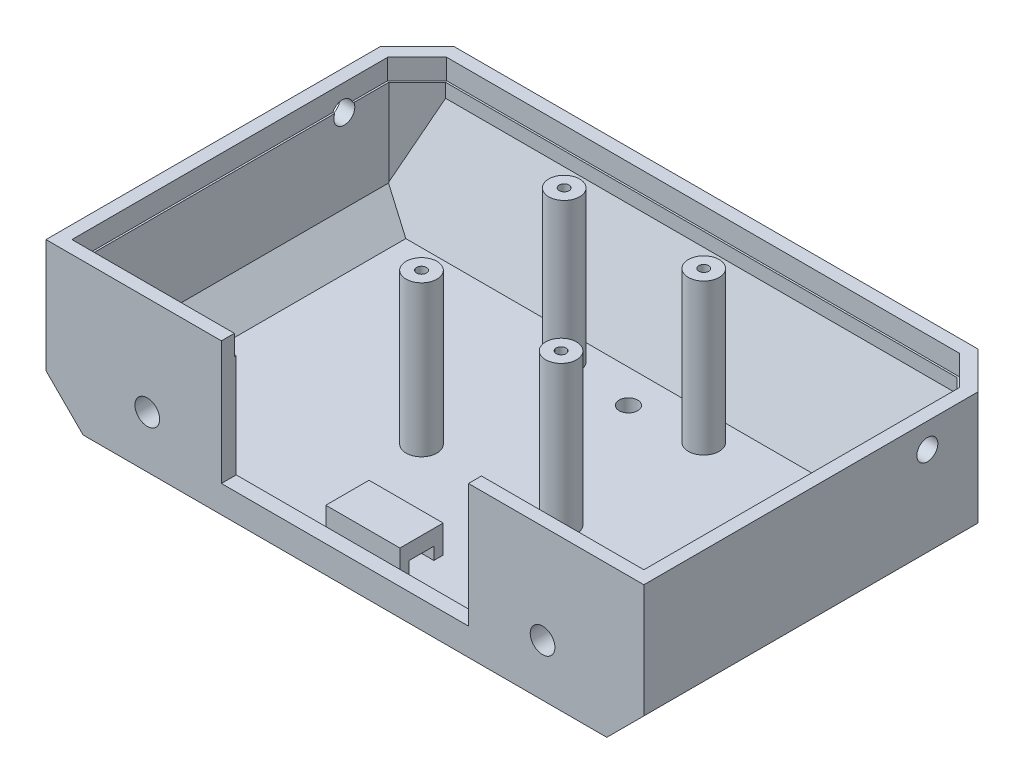
SolidWorks part; units mm, degrees
ref_plane "Front Plane" through (0, 0, 0) normal (0, 0, 1) x (1, 0, 0)
ref_plane "Top Plane" through (0, 0, 0) normal (0, 1, 0) x (1, 0, 0)
ref_plane "Right Plane" through (0, 0, 0) normal (1, 0, 0) x (0, 0, -1)
ref_plane "PZm28_4" through (0, -28.4, 0) normal (0, 1, 0) x (1, 0, 0)
sketch "Sketch1" plane through (0, -28.4, 0) normal (0, 1, 0) x (1, 0, 0)
  line L0 (-48.4, -11.9) -> (48.4, -11.9)
  line L1 (48.4, -11.9) -> (48.4, 42.2)
  line L2 (48.4, 42.2) -> (42.4, 48.2)
  line L3 (42.4, 48.2) -> (-42.4, 48.2)
  line L4 (-42.4, 48.2) -> (-48.4, 42.2)
  line L5 (-48.4, 42.2) -> (-48.4, -11.9)
extrude "Tray Block" add sketch "Sketch1" along normal blind 24.4
sketch "Sketch2" plane through (0, 0, 0) normal (1, 0, 0) x (0, 0, -1)
  line L0 (49.64, -6.32) -> (53.2, -6.32)
  line L1 (53.2, -6.32) -> (53.2, -32.08)
  line L2 (53.2, -32.08) -> (39.56, -32.08)
  line L3 (39.56, -32.08) -> (49.64, -6.32)
extrude "Lower Front Facet" cut sketch "Sketch2" against normal through all and the other way through all
sketch "Sketch3" plane through (0, 0, 0) normal (0, 0, 1) x (1, 0, 0)
  line L0 (-49.4, -21.4) -> (-49.4, -29.4)
  line L1 (-49.4, -29.4) -> (-41.4, -29.4)
  line L2 (-41.4, -29.4) -> (-49.4, -21.4)
extrude "Lower Side Facet L" cut sketch "Sketch3" against normal through all and the other way through all
sketch "Sketch4" plane through (0, 0, 0) normal (0, 0, 1) x (1, 0, 0)
  line L0 (49.4, -21.4) -> (49.4, -29.4)
  line L1 (49.4, -29.4) -> (41.4, -29.4)
  line L2 (41.4, -29.4) -> (49.4, -21.4)
extrude "Lower Side Facet R" cut sketch "Sketch4" against normal through all and the other way through all
shell "Shell" thickness 2.4
ref_plane "PZm7_3" through (0, -7.3, 0) normal (0, 1, 0) x (1, 0, 0)
sketch "Sketch5" plane through (0, -7.3, 0) normal (0, 1, 0) x (1, 0, 0)
  line L0 (-46.3, -9.8) -> (46.3, -9.8)
  line L1 (46.3, -9.8) -> (46.3, 41.3302)
  line L2 (46.3, 41.3302) -> (41.5302, 46.1)
  line L3 (41.5302, 46.1) -> (-41.5302, 46.1)
  line L4 (-41.5302, 46.1) -> (-46.3, 41.3302)
  line L5 (-46.3, 41.3302) -> (-46.3, -9.8)
extrude "Seam Rebate" cut sketch "Sketch5" along normal blind 4.3
ref_plane "PZm26_5" through (0, -26.5, 0) normal (0, 1, 0) x (1, 0, 0)
sketch "Sketch6" plane through (0, -26.5, 0) normal (0, 1, 0) x (1, 0, 0)
  circle A0 centre (-11.3, 11.8) radius 2.5
  circle A1 centre (-11.3, 34.9) radius 2.5
  circle A2 centre (11.3, 11.8) radius 2.5
  circle A3 centre (11.3, 34.9) radius 2.5
extrude "Board Pillars" add sketch "Sketch6" along normal blind 24.9
ref_plane "PZm9_6" through (0, -9.6, 0) normal (0, 1, 0) x (1, 0, 0)
sketch "Sketch7" plane through (0, -9.6, 0) normal (0, 1, 0) x (1, 0, 0)
  circle A0 centre (-11.3, 11.8) radius 0.8
  circle A1 centre (-11.3, 34.9) radius 0.8
  circle A2 centre (11.3, 11.8) radius 0.8
  circle A3 centre (11.3, 34.9) radius 0.8
extrude "Board Pilots" cut sketch "Sketch7" along normal blind 8.5
ref_plane "PY9" through (0, 0, 9) normal (0, 0, 1) x (1, 0, 0)
sketch "Sketch8" plane through (0, 0, 9) normal (0, 0, 1) x (1, 0, 0)
  line L0 (-20, -24) -> (20, -24)
  line L1 (20, -24) -> (20, -3)
  line L2 (20, -3) -> (-20, -3)
  line L3 (-20, -3) -> (-20, -24)
extrude "Cable Window" cut sketch "Sketch8" along normal blind 3.9
ref_plane "PY3_5" through (0, 0, 3.5) normal (0, 0, 1) x (1, 0, 0)
sketch "Sketch9" plane through (0, 0, 3.5) normal (0, 0, 1) x (1, 0, 0)
  circle A0 centre (-32, -20) radius 4
  circle A1 centre (32, -20) radius 4
extrude "Flange Bosses" add sketch "Sketch9" along normal blind 6.2
ref_plane "PY5_4" through (0, 0, 5.4) normal (0, 0, 1) x (1, 0, 0)
sketch "Sketch10" plane through (0, 0, 5.4) normal (0, 0, 1) x (1, 0, 0)
  circle A0 centre (-32, -20) radius 2
  circle A1 centre (32, -20) radius 2
extrude "Flange Insert Holes" cut sketch "Sketch10" along normal blind 7
ref_plane "PXm49_4" through (-49.4, 0, 0) normal (1, 0, 0) x (0, 0, -1)
sketch "Sketch11" plane through (-49.4, 0, 0) normal (1, 0, 0) x (0, 0, -1)
  circle A0 centre (34, -8) radius 1.7
extrude "Seam Screw Hole L" cut sketch "Sketch11" along normal blind 3.9
ref_plane "PX45_5" through (45.5, 0, 0) normal (1, 0, 0) x (0, 0, -1)
sketch "Sketch12" plane through (45.5, 0, 0) normal (1, 0, 0) x (0, 0, -1)
  circle A0 centre (34, -8) radius 1.7
extrude "Seam Screw Hole R" cut sketch "Sketch12" along normal blind 3.9
sketch "Sketch13" plane through (0, -26.5, 0) normal (0, 1, 0) x (1, 0, 0)
  line L0 (-6, -9) -> (6, -9)
  line L1 (6, -9) -> (6, -2)
  line L2 (6, -2) -> (-6, -2)
  line L3 (-6, -2) -> (-6, -9)
extrude "Bundle Tie Anchor" add sketch "Sketch13" along normal blind 5
ref_plane "PXm7" through (-7, 0, 0) normal (1, 0, 0) x (0, 0, -1)
sketch "Sketch14" plane through (-7, 0, 0) normal (1, 0, 0) x (0, 0, -1)
  line L0 (-7.5, -26) -> (-3.5, -26)
  line L1 (-3.5, -26) -> (-3.5, -24)
  line L2 (-3.5, -24) -> (-7.5, -24)
  line L3 (-7.5, -24) -> (-7.5, -26)
extrude "Bundle Tie Slot" cut sketch "Sketch14" along normal blind 14
ref_plane "PZm29_4" through (0, -29.4, 0) normal (0, 1, 0) x (1, 0, 0)
sketch "Sketch15" plane through (0, -29.4, 0) normal (0, 1, 0) x (1, 0, 0)
  circle A0 centre (0, 34) radius 1.5
extrude "Drain Hole" cut sketch "Sketch15" along normal blind 3.9
equation "\"BOARD_REAR\" = 86.0"
equation "\"BOARD_FRONT\" = 41.0"
equation "\"BOARD_END\" = 22.0"
equation "\"BOARD_ANGLED\" = 30.0"
equation "\"BOARD_DEPTH\" = 41.8431"
equation "\"PCB_T\" = 1.6"
equation "\"ABOVE_PCB\" = 14.0"
equation "\"BELOW_PCB\" = 6.0"
equation "\"MID_PARTS_H\" = 9.0"
equation "\"BOARD_HOLE_PILOT\" = 1.6"
equation "\"J2_X\" = 19.0"
equation "\"DUPONT_DROP\" = 14.0"
equation "\"BEND_R\" = 5.0"
equation "\"BOARD_GAP\" = 3.0"
equation "\"TOF_FOV\" = 25.0"
equation "\"TOF_MARGIN_DEG\" = 5.0"
equation "\"TOF_WIN_MARGIN\" = 1.0"
equation "\"TOF_Z\" = 9.0"
equation "\"TOF_SIDE_BEARING\" = 90.0"
equation "\"TOF_CONE_LEN\" = 70.0"
equation "\"CAM_W\" = 29.2"
equation "\"CAM_H\" = 28.2"
equation "\"CAM_D\" = 12.35"
equation "\"CAM_FRONT_Y\" = 43.0"
equation "\"CAM_BOTTOM_Z\" = 17.0"
equation "\"CAM_LENS_UP\" = 11.6"
equation "\"CAM_LENS_OPEN\" = 9.6"
equation "\"CAM_HFOV\" = 53.5"
equation "\"CAM_VFOV\" = 41.41"
equation "\"CAM_FOV_MARGIN\" = 3.0"
equation "\"CAM_FIT\" = 0.3"
equation "\"RIBBON_W\" = 16.0"
equation "\"RIBBON_T\" = 0.3"
equation "\"RIBBON_LEN\" = 150.0"
equation "\"RIBBON_EXIT_Y\" = 35.0"
equation "\"WALL\" = 2.4"
equation "\"HEAD_X\" = 48.4"
equation "\"HEAD_REAR_Y\" = -11.9"
equation "\"CAM_FOAM\" = 2.8"
equation "\"HEAD_FRONT_Y\" = 48.2"
equation "\"HEAD_TOP_Z\" = 50.6"
equation "\"HEAD_BOT_Z\" = -28.4"
equation "\"HEAD_SPLIT_Z\" = -4.0"
equation "\"SKIRT_T\" = 1.2"
equation "\"SKIRT_H\" = 3.0"
equation "\"SKIRT_FIT\" = 0.3"
equation "\"VISOR\" = 7.8"
equation "\"VISOR_Z\" = 40.0"
equation "\"ROOF_SLOPE_Y\" = 40.0"
equation "\"ROOF_CHAMFER\" = 10.0"
equation "\"REAR_CHAMFER\" = 10.0"
equation "\"CORNER_CHAMFER\" = 6.0"
equation "\"LOWER_SIDE_FACET\" = 6.0"
equation "\"LIGHTBAR_DEPTH\" = 1.0"
equation "\"HOOD_Z\" = 14.0"
equation "\"HOOD_L\" = 6.0"
equation "\"SIDE_HOOD_L\" = 4.0"
equation "\"INSERT_M3_D\" = 4.0"
equation "\"INSERT_M3_L\" = 6.0"
equation "\"M3_CLEAR\" = 3.4"
equation "\"M2_PILOT\" = 1.6"
equation "\"M25_PILOT\" = 2.2"
equation "\"BOX_X\" = 72.4"
equation "\"BOX_FRONT_Y\" = -11.9"
equation "\"BOX_REAR_Y\" = -124.4"
equation "\"BOX_BOT_Z\" = -28.4"
equation "\"BOX_TOP_Z\" = 10.0"
equation "\"LID_T\" = 2.4"
equation "\"LID_SKIRT\" = 1.6"
equation "\"LID_TONGUE_H\" = 3.0"
equation "\"LID_FIT\" = 0.3"
equation "\"PI_STANDOFF\" = 8.0"
equation "\"BOX_REAR_CHAMFER\" = 8.0"
equation "\"BOX_REAR_FACET\" = 4.0"
equation "\"VENT_UPSTAND\" = 3.0"
equation "\"TUBE_D\" = 22.2"
equation "\"TUBE_LINER\" = 1.0"
equation "\"MOUNT_Y\" = -70.0"
equation "\"RAIL_W\" = 30.0"
equation "\"RAIL_W2\" = 38.0"
equation "\"RAIL_H\" = 6.0"
equation "\"SLIDE\" = 0.3"
equation "\"STOP_T\" = 6.0"
equation "\"CLAMP_W\" = 40.0"
equation "\"CLAMP_HALF\" = 20.0"
equation "\"CLAMP_DROP\" = 12.0"
equation "\"CAP_T\" = 12.0"
equation "\"CLAMP_BOLT_OFF\" = 16.6"
equation "\"M5_INSERT_D\" = 6.4"
equation "\"M5_CLEAR\" = 5.5"
equation "\"LOCK_D\" = 3.3"
equation "\"POD_TILT_DEG\" = 0.0"
equation "\"PRINT_LIMIT\" = 180.0"
equation "\"PI5_L\" = 85.0"
equation "\"PI5_W\" = 56.0"
equation "\"PI5_T\" = 1.6"
equation "\"PI5_USBC_BX\" = 11.2"
equation "\"PI5_ETH_BY\" = 10.2"
equation "\"PI5_PORT_OVERHANG\" = 3.0"
equation "\"PI5_FPC_H\" = 5.0"
equation "\"PI5_FPC_USE\" = 0.0"
equation "\"PI5_PIN1_BX\" = 8.37"
equation "\"HEADER_BASE_H\" = 2.5"
equation "\"DUPONT_L\" = 14.0"
equation "\"PI5_UNDERSIDE\" = 1.5"
equation "\"COOLER_H\" = 15.0"
equation "\"FAN_AIR_GAP_MIN\" = 8.0"
equation "\"PI_X0\" = -55.0"
equation "\"PI_Y1\" = -36.5"
equation "\"PI_Y0\" = -92.5"
equation "\"BOX_LEN\" = 112.5"
equation "\"COVER_T\" = 3.0"
equation "\"COVER_TOP_Z\" = 6.5"
equation "\"SIDE_LEDGE_Z\" = -2.5"
equation "\"RIBBON_W_PI\" = 11.5"
equation "\"RIBBON_RUN_Z\" = 8.0"
equation "\"RIBBON_SPEC_LEN\" = 200.0"
